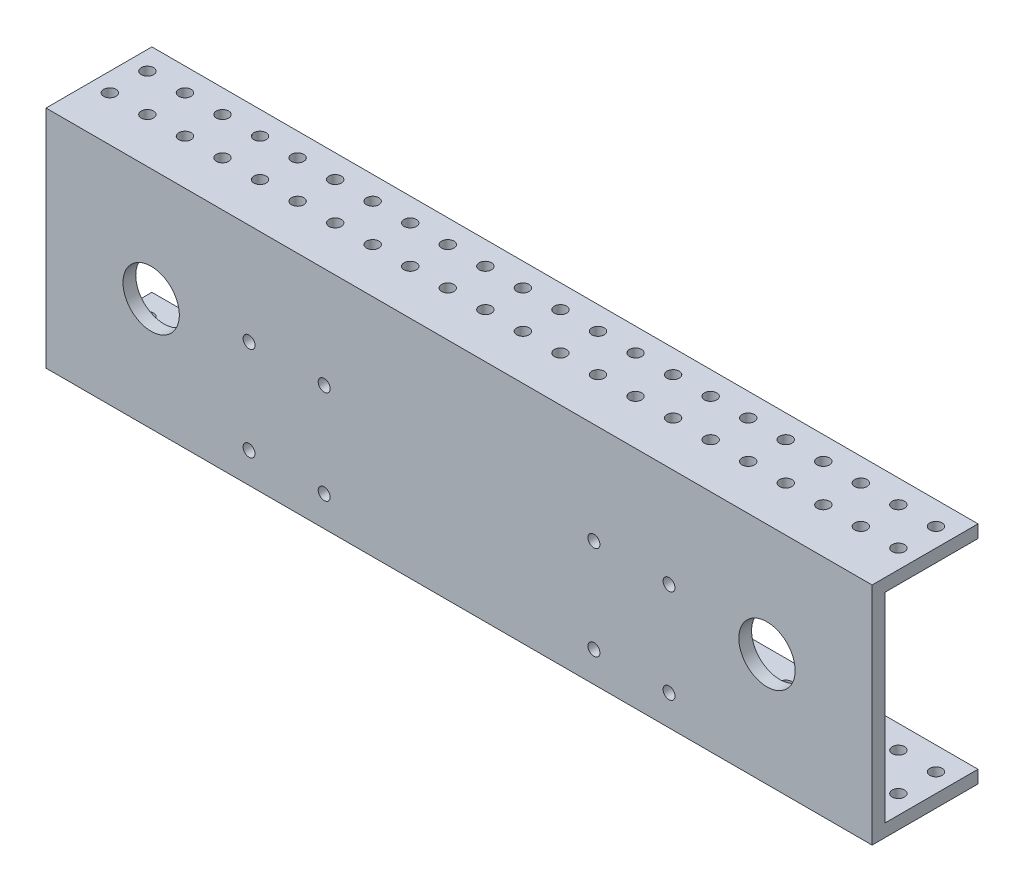
SolidWorks part; units mm, degrees
material "6061-T6 (SS)"
ref_plane "Front Plane" through (0, 0, 0) normal (0, 0, 1) x (1, 0, 0)
ref_plane "Top Plane" through (0, 0, 0) normal (0, 1, 0) x (1, 0, 0)
ref_plane "Right Plane" through (0, 0, 0) normal (1, 0, 0) x (0, 0, -1)
sketch "Sketch1" plane through (0, 0, 0) normal (1, 0, 0) x (0, 0, -1)
  line L0 (0, 38.1) -> (0, -38.1)
  line L1 (0, -38.1) -> (35.814, -38.1)
  line L2 (35.814, -38.1) -> (35.814, -33.782)
  line L3 (35.814, -33.782) -> (4.318, -33.782)
  line L4 (4.318, -33.782) -> (4.318, 33.782)
  line L5 (4.318, 33.782) -> (35.814, 33.782)
  line L6 (35.814, 33.782) -> (35.814, 38.1)
  line L7 (35.814, 38.1) -> (0, 38.1)
  dimension "D1" = 76.2
  dimension "D2" = 35.814
  dimension "D3" = 4.318
  dimension "D4" = 4.318
extrude "Boss-Extrude1" add sketch "Sketch1" along normal mid plane 279.4
sketch "Sketch2" plane through (0, 38.1, 0) normal (0, 1, 0) x (1, 0, 0)
  line L0 (-139.7, 35.814) -> (-139.7, 0) construction
  line L2 (-151.0642, 21.59) -> (-138.9022, 21.59) construction
  line L5 (139.7, 0) -> (-139.7, 0) construction
  circle A0 centre (-133.35, 27.94) radius 2.0828
  circle A1 centre (-133.35, 15.24) radius 2.0828
  circle A2 centre (-120.65, 27.94) radius 2.0828
  circle A3 centre (-120.65, 15.24) radius 2.0828
  circle A4 centre (-107.95, 27.94) radius 2.0828
  circle A5 centre (-107.95, 15.24) radius 2.0828
  circle A6 centre (-95.25, 27.94) radius 2.0828
  circle A7 centre (-95.25, 15.24) radius 2.0828
  circle A8 centre (-82.55, 27.94) radius 2.0828
  circle A9 centre (-82.55, 15.24) radius 2.0828
  circle A10 centre (-69.85, 27.94) radius 2.0828
  circle A11 centre (-69.85, 15.24) radius 2.0828
  circle A12 centre (-57.15, 27.94) radius 2.0828
  circle A13 centre (-57.15, 15.24) radius 2.0828
  circle A14 centre (-44.45, 27.94) radius 2.0828
  circle A15 centre (-44.45, 15.24) radius 2.0828
  circle A16 centre (-31.75, 27.94) radius 2.0828
  circle A17 centre (-31.75, 15.24) radius 2.0828
  circle A18 centre (-19.05, 27.94) radius 2.0828
  circle A19 centre (-19.05, 15.24) radius 2.0828
  circle A20 centre (-6.35, 27.94) radius 2.0828
  circle A21 centre (-6.35, 15.24) radius 2.0828
  circle A22 centre (6.35, 27.94) radius 2.0828
  circle A23 centre (6.35, 15.24) radius 2.0828
  circle A24 centre (19.05, 27.94) radius 2.0828
  circle A25 centre (19.05, 15.24) radius 2.0828
  circle A26 centre (31.75, 27.94) radius 2.0828
  circle A27 centre (31.75, 15.24) radius 2.0828
  circle A28 centre (44.45, 27.94) radius 2.0828
  circle A29 centre (44.45, 15.24) radius 2.0828
  circle A30 centre (57.15, 27.94) radius 2.0828
  circle A31 centre (57.15, 15.24) radius 2.0828
  circle A32 centre (69.85, 27.94) radius 2.0828
  circle A33 centre (69.85, 15.24) radius 2.0828
  circle A34 centre (82.55, 27.94) radius 2.0828
  circle A35 centre (82.55, 15.24) radius 2.0828
  circle A36 centre (95.25, 27.94) radius 2.0828
  circle A37 centre (95.25, 15.24) radius 2.0828
  circle A38 centre (107.95, 27.94) radius 2.0828
  circle A39 centre (107.95, 15.24) radius 2.0828
  circle A40 centre (120.65, 27.94) radius 2.0828
  circle A41 centre (120.65, 15.24) radius 2.0828
  circle A42 centre (133.35, 27.94) radius 2.0828
  circle A43 centre (133.35, 15.24) radius 2.0828
  circle A48 centre (146.05, 27.94) radius 2.0828 [skipped]
  circle A49 centre (146.05, 15.24) radius 2.0828 [skipped]
  circle A50 centre (158.75, 27.94) radius 2.0828 [skipped]
  circle A51 centre (158.75, 15.24) radius 2.0828 [skipped]
  dimension "D1" = 12.7
  dimension "D2" = 4.1656
  dimension "D3" = 6.35
  dimension "D4" = 24
  dimension "D5" = 12.7
  dimension "D6" = 21.59
extrude "Cut-Extrude1" cut sketch "Sketch2" against normal through all
sketch "Sketch4" plane through (0, 0, 0) normal (0, 0, 1) x (1, 0, 0)
  circle A0 centre (45.6167, -27.825) radius 2.0193 construction
  circle A1 centre (-71.0167, 3.925) radius 2.0193
  circle A2 centre (-71.0167, 3.925) radius 2.0193
  circle A3 centre (-45.6167, -27.825) radius 2.0193
  circle A4 centre (-45.6167, -27.825) radius 2.0193
  circle A5 centre (-45.6167, 3.925) radius 2.0193
  circle A6 centre (-45.6167, 3.925) radius 2.0193
  circle A7 centre (-71.0167, -27.825) radius 2.0193
  circle A8 centre (-71.0167, -27.825) radius 2.0193
  circle A9 centre (71.0167, -27.825) radius 2.0193 construction
  circle A10 centre (71.0167, 3.925) radius 2.0193 construction
  circle A11 centre (45.6167, 3.925) radius 2.0193 construction
  circle A12 centre (45.6167, -27.825) radius 2.0193
  circle A13 centre (71.0167, -27.825) radius 2.0193
  circle A14 centre (71.0167, 3.925) radius 2.0193
  circle A15 centre (45.6167, 3.925) radius 2.0193
  dimension "D1" = 0
  dimension "D2" = 0
  dimension "D3" = 0
  dimension "D4" = 0
extrude "Cut-Extrude3" cut sketch "Sketch4" against normal up to next
sketch "Sketch5" plane through (0, 0, -4.318) normal (0, 0, -1) x (-1, 0, 0)
  line L0 (139.7, 0) -> (-139.7, 0) construction
  line L1 (139.7, -33.782) -> (139.7, 33.782) construction
  line L2 (-139.7, -33.782) -> (-139.7, 33.782) construction
  line L3 (-139.7, -33.782) -> (139.7, -33.782) construction
  line L4 (-27.94, 33.782) -> (27.94, 33.782) construction
  line L5 (-27.94, 33.782) -> (-27.94, -33.782) construction
  line L6 (-27.94, -33.782) -> (27.94, -33.782) construction
  line L7 (27.94, 33.782) -> (27.94, -33.782) construction
  line L8 (-139.7, 33.782) -> (139.7, 33.782) construction
  line L9 (-27.94, 33.782) -> (27.94, -33.782) construction
  line L10 (-27.94, -33.782) -> (27.94, 33.782) construction
  circle A0 centre (104.14, 0) radius 9.525
  circle A1 centre (-104.14, 0) radius 9.525
  point P14 (0, 0)
  dimension "D2" = 19.05
  dimension "D1" = 55.88
  dimension "D3" = 76.2
  dimension "D4" = 76.2
extrude "Cut-Extrude4" cut sketch "Sketch5" against normal through all
equation "\"D3@Sketch5\"=\"D4@Sketch5\""
